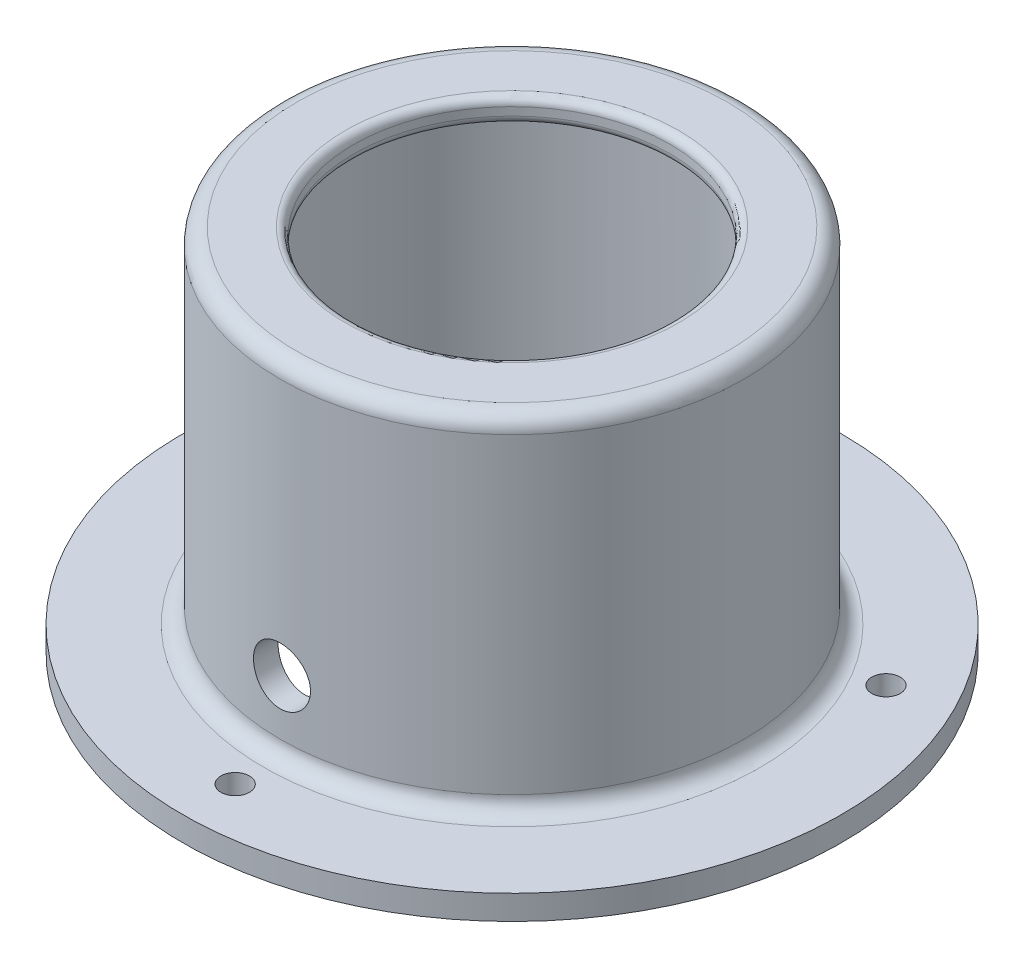
SolidWorks part; units mm, degrees
ref_plane "Front Plane" through (0, 0, 0) normal (0, 0, 1) x (1, 0, 0)
ref_plane "Top Plane" through (0, 0, 0) normal (0, 1, 0) x (1, 0, 0)
ref_plane "Right Plane" through (0, 0, 0) normal (1, 0, 0) x (0, 0, -1)
sketch "Sketch1" plane through (0, 0, 0) normal (0, 0, 1) x (1, 0, 0)
  line L0 (0, 0) -> (0, 25.4559) construction
  line L1 (-19.465, 45.275) -> (-19.465, 42.275)
  line L2 (-19.465, 42.275) -> (-25.465, 42.275)
  line L3 (-25.465, 42.275) -> (-25.465, 0)
  line L4 (-25.465, 0) -> (-40.465, 0)
  line L5 (-40.465, 0) -> (-40.465, 3)
  line L6 (-40.465, 3) -> (-28.465, 3)
  line L7 (-28.465, 3) -> (-28.465, 45.275)
  line L8 (-28.465, 45.275) -> (-19.465, 45.275)
  point P11 (-40.6414, 42.275)
  dimension "D1" = 3
  dimension "D2" = 3
  dimension "D3" = 3
  dimension "D4" = 42.275
  dimension "D5" = 25.465
  dimension "D6" = 12
  dimension "D7" = 6
revolve "Revolve1" add sketch "Sketch1" angle 360 about L0
fillet "Fillet1" radius 2 2 edges at (0, 42.275, -25.465) (0, 45.275, -28.465)
sketch "Sketch2" plane through (0, 3, 0) normal (0, 1, 0) x (1, 0, 0)
  line L0 (0, 0) -> (0, -34) construction
  circle A0 centre (0, -34) radius 1.75
  circle A2 centre (-28.9815, 16.7325) radius 1.75
  circle A3 centre (29.4449, 16.465) radius 1.75
  circle A4 centre (0, 0) radius 40.465 construction
  point P13 (0.1544, -0.2675)
  dimension "D1" = 3.5
  dimension "D3" = 34
  dimension "D2" = 3
extrude "Cut-Extrude1" cut sketch "Sketch2" against normal through all both and the other way through all
fillet "Fillet2" radius 2 2 edges at (0, 0, -25.465) (0, 3, -28.465)
fillet "Fillet3" radius 1 2 edges at (0, 42.275, -19.465) (0, 45.275, -19.465)
sketch "Sketch3" plane through (0, 0, 0) normal (0, 0, 1) x (1, 0, 0)
  line L0 (7.5, 11.74) -> (-7.5, 11.74) construction
  line L1 (7.5, 8.24) -> (-7.5, 8.24)
  line L2 (7.5, 15.24) -> (-7.5, 15.24)
  line L3 (-40.465, 0) -> (40.465, 0) construction
  line L4 (0, 0) -> (0, 22.7785) construction
  arc A0 (7.5, 8.24) -> (7.5, 15.24) centre (7.5, 11.74) ccw
  arc A1 (-7.5, 15.24) -> (-7.5, 8.24) centre (-7.5, 11.74) ccw
  point P2 (0, 11.74)
  point P11 (0, 0)
  point P12 (0, 0)
  dimension "D1" = 15.24
  dimension "D2" = 7
  dimension "D3" = 15
extrude "Cut-Extrude2" cut sketch "Sketch3" against normal through all
sketch "Sketch4" plane through (0, 0, 0) normal (0, 0, 1) x (1, 0, 0)
  line L0 (0, 0) -> (0, 45.275) construction
  line L1 (20.465, 45.275) -> (-20.465, 45.275) construction
  line L4 (-40.465, 0) -> (40.465, 0) construction
  circle A0 centre (0, 11.74) radius 3.5
  point P7 (0, 15.24)
  dimension "D1" = 7
  dimension "D2" = 15.24
extrude "Cut-Extrude3" cut sketch "Sketch4" along normal through all
